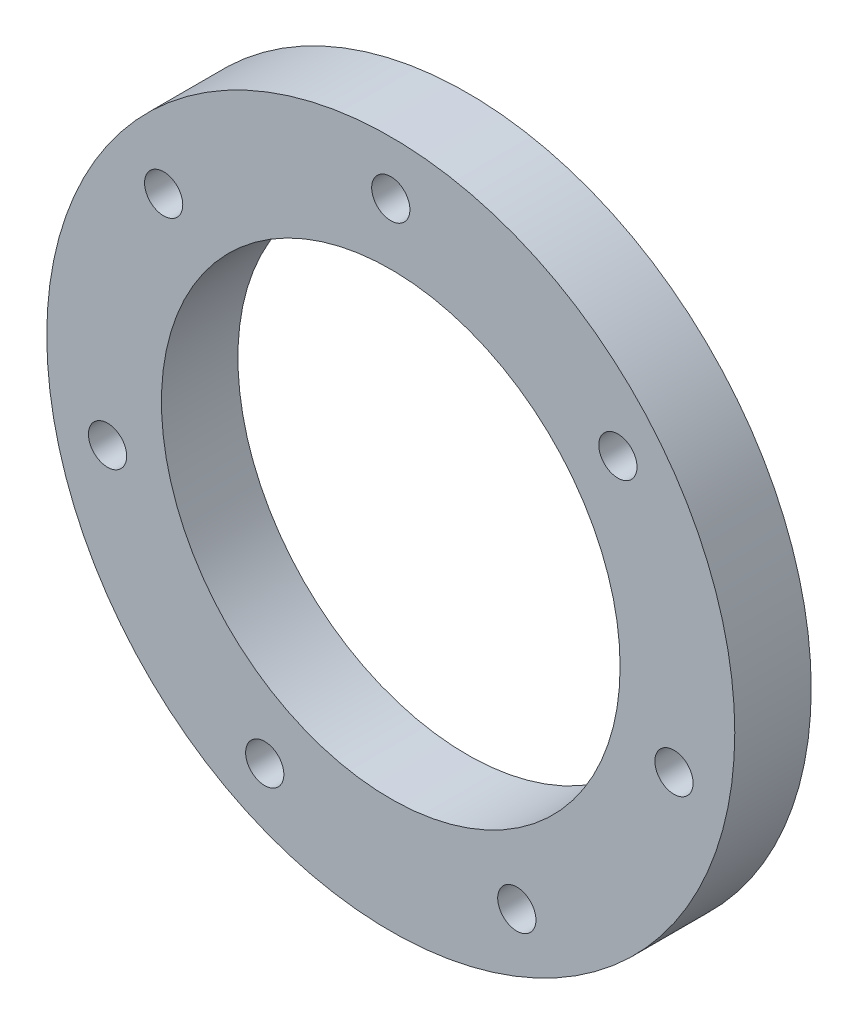
SolidWorks part; units mm, degrees
ref_plane "Front Plane" through (0, 0, 0) normal (0, 0, 1) x (1, 0, 0)
ref_plane "Top Plane" through (0, 0, 0) normal (0, 1, 0) x (1, 0, 0)
ref_plane "Right Plane" through (0, 0, 0) normal (1, 0, 0) x (0, 0, -1)
sketch "Sketch1" plane through (0, 0, 0) normal (0, 0, 1) x (1, 0, 0)
  line L0 (0, 0) -> (0, 19) construction
  circle A0 centre (0, 0) radius 22.5
  circle A1 centre (0, 0) radius 19 construction
  circle A2 centre (0, 19) radius 1.25
  circle A3 centre (14.8548, 11.8463) radius 1.25
  circle A4 centre (18.5236, -4.2279) radius 1.25
  circle A5 centre (8.2438, -17.1184) radius 1.25
  circle A6 centre (-8.2438, -17.1184) radius 1.25
  circle A7 centre (-18.5236, -4.2279) radius 1.25
  circle A8 centre (0, 0) radius 15
  circle A9 centre (-14.8548, 11.8463) radius 1.25
  point P19 (0, 0)
  dimension "D1" = 38
  dimension "D2" = 45
  dimension "D3" = 2.5
  dimension "D5" = 30
  dimension "D4" = 7
extrude "Boss-Extrude1" add sketch "Sketch1" along normal blind 5
